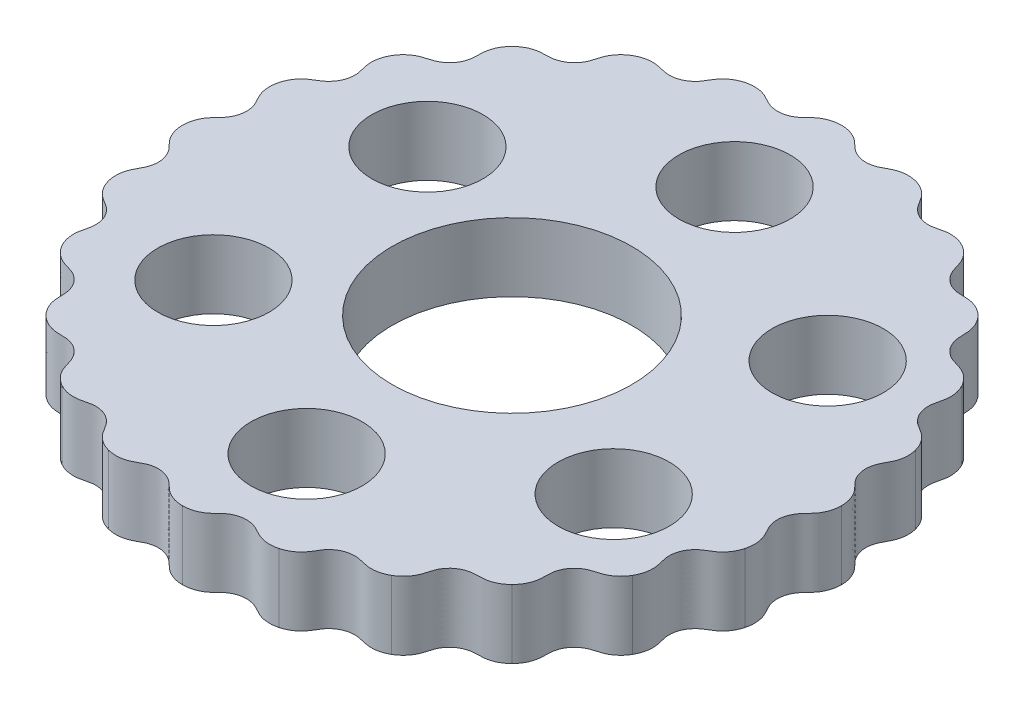
SolidWorks part; units mm, degrees
ref_plane "Front Plane" through (0, 0, 0) normal (0, 0, 1) x (1, 0, 0)
ref_plane "Top Plane" through (0, 0, 0) normal (0, 1, 0) x (1, 0, 0)
ref_plane "Right Plane" through (0, 0, 0) normal (1, 0, 0) x (0, 0, -1)
sketch "Sketch1" plane through (0, 0, 0) normal (0, 1, 0) x (1, 0, 0)
  line L0 (0, 0) -> (-1, 0) construction
  line L1 (40, 0) -> (41, 0) construction
  line L2 (-1, 0) -> (-1, 26) construction
  circle A0 centre (0, 0) radius 40 construction
  circle A1 centre (40, 0) radius 2.5 construction
  circle A2 centre (38.7433, -9.9476) radius 2.5 construction
  circle A3 centre (35.0523, -19.2701) radius 2.5 construction
  circle A4 centre (29.1587, -27.3819) radius 2.5 construction
  circle A5 centre (21.4331, -33.7731) radius 2.5 construction
  circle A6 centre (12.3607, -38.0423) radius 2.5 construction
  circle A7 centre (2.5116, -39.9211) radius 2.5 construction
  circle A8 centre (-7.4953, -39.2915) radius 2.5 construction
  circle A9 centre (-17.0312, -36.1931) radius 2.5 construction
  circle A10 centre (-25.497, -30.8205) radius 2.5 construction
  circle A11 centre (-32.3607, -23.5114) radius 2.5 construction
  circle A12 centre (-37.1911, -14.725) radius 2.5 construction
  circle A13 centre (-39.6846, -5.0133) radius 2.5 construction
  circle A14 centre (-39.6846, 5.0133) radius 2.5 construction
  circle A15 centre (-37.1911, 14.725) radius 2.5 construction
  circle A16 centre (-32.3607, 23.5114) radius 2.5 construction
  circle A17 centre (-25.497, 30.8205) radius 2.5 construction
  circle A18 centre (-17.0312, 36.1931) radius 2.5 construction
  circle A19 centre (-7.4953, 39.2915) radius 2.5 construction
  circle A20 centre (2.5116, 39.9211) radius 2.5 construction
  circle A21 centre (12.3607, 38.0423) radius 2.5 construction
  circle A22 centre (21.4331, 33.7731) radius 2.5 construction
  circle A23 centre (29.1587, 27.3819) radius 2.5 construction
  circle A24 centre (35.0523, 19.2701) radius 2.5 construction
  circle A25 centre (38.7433, 9.9476) radius 2.5 construction
  circle A26 centre (0, 0) radius 38.4 construction
  circle A27 centre (38.637, 10.3528) radius 1.6 construction
  circle A28 centre (39.603, 10.6116) radius 0.25 construction
  circle A29 centre (-1, 0) radius 14
  circle A30 centre (-1, 26) radius 6.5
  circle A31 centre (22.0167, 13.866) radius 6.5
  circle A32 centre (23.0167, -12.134) radius 6.5
  circle A33 centre (1, -26) radius 6.5
  circle A34 centre (-22.0167, -13.866) radius 6.5
  circle A35 centre (-23.0167, 12.134) radius 6.5
  spline S48 degree 3 poles (-38.1881, 9.9647) (-38.1134, 10.2441) (-37.9518, 10.654) (-37.653, 11.1446) (-37.3903, 11.4799) (-37.1455, 11.7256) (-36.9277, 11.9083) (-36.7529, 12.0385) (-36.5906, 12.1462) (-36.4589, 12.2267) (-36.305, 12.3174) (-36.1077, 12.438) (-35.8562, 12.5947) (-35.414, 12.9369) (-35.0082, 13.4243) (-34.7303, 13.9227) (-34.557, 14.4369) (-34.4576, 15.2234) (-34.5769, 15.8673) (-34.6328, 16.0713) (-34.6733, 16.2389) (-34.7113, 16.3925) (-34.7527, 16.5721) (-34.7948, 16.7807) (-34.8258, 16.9881) (-34.85, 17.2627) (-34.8492, 17.6154) (-34.7979, 18.0376) (-34.6627, 18.5948) (-34.4867, 18.9996) (-34.3419, 19.2502) knots -0.000084 -0.000084 -0.000084 -0.000084 0.124937 0.187447 0.249958 0.312468 0.343724 0.374979 0.406234 0.421862 0.437489 0.453117 0.468745 0.484372 0.492186 0.5 0.507814 0.515628 0.531255 0.546883 0.562511 0.578138 0.593766 0.625021 0.656276 0.687532 0.750042 0.812553 0.875063 1.000084 1.000084 1.000084 1.000084
  spline S49 degree 3 poles (-34.3419, 19.2502) (-34.1974, 19.5007) (-33.9353, 19.8548) (-33.5196, 20.2513) (-33.1791, 20.5073) (-32.879, 20.6812) (-32.6214, 20.8013) (-32.4189, 20.8818) (-32.2342, 20.9438) (-32.0861, 20.9876) (-31.914, 21.0353) (-31.6923, 21.1008) (-31.4088, 21.187) (-30.893, 21.4031) (-30.3749, 21.7688) (-29.9775, 22.1783) (-29.677, 22.6302) (-29.3775, 23.3642) (-29.326, 24.017) (-29.3272, 24.2285) (-29.323, 24.4009) (-29.3199, 24.559) (-29.3134, 24.7432) (-29.3001, 24.9557) (-29.2764, 25.164) (-29.2287, 25.4355) (-29.1366, 25.776) (-28.9778, 26.1705) (-28.703, 26.6737) (-28.4282, 27.0192) (-28.2235, 27.2237) knots -0.000084 -0.000084 -0.000084 -0.000084 0.124937 0.187447 0.249958 0.312468 0.343724 0.374979 0.406234 0.421862 0.437489 0.453117 0.468745 0.484372 0.492186 0.5 0.507814 0.515628 0.531255 0.546883 0.562511 0.578138 0.593766 0.625021 0.656276 0.687532 0.750042 0.812553 0.875063 1.000084 1.000084 1.000084 1.000084
  spline S50 degree 3 poles (-28.2235, 27.2237) (-28.0191, 27.4283) (-27.6742, 27.7026) (-27.1701, 27.978) (-26.7749, 28.1371) (-26.4401, 28.2274) (-26.1602, 28.2767) (-25.9437, 28.3021) (-25.7492, 28.3142) (-25.5949, 28.3181) (-25.4163, 28.3197) (-25.1852, 28.3255) (-24.889, 28.3354) (-24.3349, 28.4107) (-23.7398, 28.6298) (-23.25, 28.9226) (-22.8428, 29.2812) (-22.3634, 29.9127) (-22.1448, 30.5299) (-22.0912, 30.7346) (-22.0425, 30.9) (-21.9986, 31.0519) (-21.9447, 31.2282) (-21.8768, 31.43) (-21.8, 31.625) (-21.6836, 31.8749) (-21.5066, 32.18) (-21.251, 32.5199) (-20.8553, 32.9349) (-20.5005, 33.1974) (-20.2498, 33.3421) knots -0.000084 -0.000084 -0.000084 -0.000084 0.124937 0.187447 0.249958 0.312468 0.343724 0.374979 0.406234 0.421862 0.437489 0.453117 0.468745 0.484372 0.492186 0.5 0.507814 0.515628 0.531255 0.546883 0.562511 0.578138 0.593766 0.625021 0.656276 0.687532 0.750042 0.812553 0.875063 1.000084 1.000084 1.000084 1.000084
  spline S51 degree 3 poles (-20.2498, 33.3421) (-19.9994, 33.4868) (-19.5954, 33.6624) (-19.0372, 33.798) (-18.6143, 33.8494) (-18.2675, 33.85) (-17.9843, 33.8252) (-17.7687, 33.7936) (-17.5777, 33.755) (-17.4276, 33.7188) (-17.2547, 33.6741) (-17.0299, 33.6199) (-16.7413, 33.5529) (-16.1866, 33.4821) (-15.555, 33.5398) (-15.0061, 33.6958) (-14.52, 33.9368) (-13.8935, 34.4227) (-13.5226, 34.9623) (-13.4179, 35.1461) (-13.328, 35.2933) (-13.2462, 35.4287) (-13.1485, 35.585) (-13.0308, 35.7623) (-12.9061, 35.9308) (-12.729, 36.1421) (-12.479, 36.391) (-12.1442, 36.6532) (-11.6546, 36.9516) (-11.2439, 37.1134) (-10.9644, 37.1882) knots -0.000084 -0.000084 -0.000084 -0.000084 0.124937 0.187447 0.249958 0.312468 0.343724 0.374979 0.406234 0.421862 0.437489 0.453117 0.468745 0.484372 0.492186 0.5 0.507814 0.515628 0.531255 0.546883 0.562511 0.578138 0.593766 0.625021 0.656276 0.687532 0.750042 0.812553 0.875063 1.000084 1.000084 1.000084 1.000084
  spline S52 degree 3 poles (-10.9644, 37.1882) (-10.685, 37.2632) (-10.2493, 37.3283) (-9.675, 37.3147) (-9.2532, 37.2549) (-8.9181, 37.1657) (-8.651, 37.0685) (-8.4509, 36.9822) (-8.2764, 36.8954) (-8.1408, 36.8217) (-7.9853, 36.7337) (-7.7822, 36.6232) (-7.5208, 36.4837) (-7.0033, 36.2718) (-6.3783, 36.1641) (-5.8077, 36.1727) (-5.2758, 36.2797) (-4.5449, 36.5868) (-4.047, 37.0121) (-3.8982, 37.1625) (-3.7734, 37.2814) (-3.6593, 37.391) (-3.5245, 37.5167) (-3.3649, 37.6576) (-3.2008, 37.7881) (-2.9751, 37.9463) (-2.6692, 38.122) (-2.2779, 38.2886) (-1.7278, 38.4501) (-1.2892, 38.5001) (-0.9998, 38.5) knots -0.000084 -0.000084 -0.000084 -0.000084 0.124937 0.187447 0.249958 0.312468 0.343724 0.374979 0.406234 0.421862 0.437489 0.453117 0.468745 0.484372 0.492186 0.5 0.507814 0.515628 0.531255 0.546883 0.562511 0.578138 0.593766 0.625021 0.656276 0.687532 0.750042 0.812553 0.875063 1.000084 1.000084 1.000084 1.000084
  spline S53 degree 3 poles (-0.9998, 38.5) (-0.7106, 38.5001) (-0.2728, 38.4502) (0.2783, 38.2885) (0.6703, 38.1215) (0.9709, 37.9486) (1.2037, 37.7856) (1.3747, 37.6505) (1.5208, 37.5215) (1.6327, 37.4152) (1.7601, 37.29) (1.9277, 37.1307) (2.1441, 36.9283) (2.5891, 36.5896) (3.1649, 36.3238) (3.7182, 36.1844) (4.2598, 36.1501) (5.0452, 36.2577) (5.6363, 36.5395) (5.8189, 36.6464) (5.9703, 36.7289) (6.1088, 36.8053) (6.2716, 36.8918) (6.4622, 36.9865) (6.6544, 37.0701) (6.9134, 37.1645) (7.2543, 37.255) (7.6754, 37.3147) (8.2486, 37.3283) (8.6852, 37.2631) (8.9647, 37.1881) knots -0.000084 -0.000084 -0.000084 -0.000084 0.124937 0.187447 0.249958 0.312468 0.343724 0.374979 0.406234 0.421862 0.437489 0.453117 0.468745 0.484372 0.492186 0.5 0.507814 0.515628 0.531255 0.546883 0.562511 0.578138 0.593766 0.625021 0.656276 0.687532 0.750042 0.812553 0.875063 1.000084 1.000084 1.000084 1.000084
  spline S54 degree 3 poles (8.9647, 37.1881) (9.2441, 37.1134) (9.654, 36.9518) (10.1446, 36.653) (10.4799, 36.3903) (10.7256, 36.1455) (10.9083, 35.9277) (11.0385, 35.7529) (11.1462, 35.5906) (11.2267, 35.4589) (11.3174, 35.305) (11.438, 35.1077) (11.5947, 34.8562) (11.9369, 34.414) (12.4243, 34.0082) (12.9227, 33.7303) (13.4369, 33.557) (14.2234, 33.4576) (14.8673, 33.5769) (15.0713, 33.6328) (15.2389, 33.6733) (15.3925, 33.7113) (15.5721, 33.7527) (15.7807, 33.7948) (15.9881, 33.8258) (16.2627, 33.85) (16.6154, 33.8492) (17.0376, 33.7979) (17.5948, 33.6627) (17.9996, 33.4867) (18.2502, 33.3419) knots -0.000084 -0.000084 -0.000084 -0.000084 0.124937 0.187447 0.249958 0.312468 0.343724 0.374979 0.406234 0.421862 0.437489 0.453117 0.468745 0.484372 0.492186 0.5 0.507814 0.515628 0.531255 0.546883 0.562511 0.578138 0.593766 0.625021 0.656276 0.687532 0.750042 0.812553 0.875063 1.000084 1.000084 1.000084 1.000084
  spline S55 degree 3 poles (18.2502, 33.3419) (18.5007, 33.1974) (18.8548, 32.9353) (19.2513, 32.5196) (19.5073, 32.1791) (19.6812, 31.879) (19.8013, 31.6214) (19.8818, 31.4189) (19.9438, 31.2342) (19.9876, 31.0861) (20.0353, 30.914) (20.1008, 30.6923) (20.187, 30.4088) (20.4031, 29.893) (20.7688, 29.3749) (21.1783, 28.9775) (21.6302, 28.677) (22.3642, 28.3775) (23.017, 28.326) (23.2285, 28.3272) (23.4009, 28.323) (23.559, 28.3199) (23.7432, 28.3134) (23.9557, 28.3001) (24.164, 28.2764) (24.4355, 28.2287) (24.776, 28.1366) (25.1705, 27.9778) (25.6737, 27.703) (26.0192, 27.4282) (26.2237, 27.2235) knots -0.000084 -0.000084 -0.000084 -0.000084 0.124937 0.187447 0.249958 0.312468 0.343724 0.374979 0.406234 0.421862 0.437489 0.453117 0.468745 0.484372 0.492186 0.5 0.507814 0.515628 0.531255 0.546883 0.562511 0.578138 0.593766 0.625021 0.656276 0.687532 0.750042 0.812553 0.875063 1.000084 1.000084 1.000084 1.000084
  spline S56 degree 3 poles (26.2237, 27.2235) (26.4283, 27.0191) (26.7026, 26.6742) (26.978, 26.1701) (27.1371, 25.7749) (27.2274, 25.4401) (27.2767, 25.1602) (27.3021, 24.9437) (27.3142, 24.7492) (27.3181, 24.5949) (27.3197, 24.4163) (27.3255, 24.1852) (27.3354, 23.889) (27.4107, 23.3349) (27.6298, 22.7398) (27.9226, 22.25) (28.2812, 21.8428) (28.9127, 21.3634) (29.5299, 21.1448) (29.7346, 21.0912) (29.9, 21.0425) (30.0519, 20.9986) (30.2282, 20.9447) (30.43, 20.8768) (30.625, 20.8) (30.8749, 20.6836) (31.18, 20.5066) (31.5199, 20.251) (31.9349, 19.8553) (32.1974, 19.5005) (32.3421, 19.2498) knots -0.000084 -0.000084 -0.000084 -0.000084 0.124937 0.187447 0.249958 0.312468 0.343724 0.374979 0.406234 0.421862 0.437489 0.453117 0.468745 0.484372 0.492186 0.5 0.507814 0.515628 0.531255 0.546883 0.562511 0.578138 0.593766 0.625021 0.656276 0.687532 0.750042 0.812553 0.875063 1.000084 1.000084 1.000084 1.000084
  spline S57 degree 3 poles (32.3421, 19.2498) (32.4868, 18.9994) (32.6624, 18.5954) (32.798, 18.0372) (32.8494, 17.6143) (32.85, 17.2675) (32.8252, 16.9843) (32.7936, 16.7687) (32.755, 16.5777) (32.7188, 16.4276) (32.6741, 16.2547) (32.6199, 16.0299) (32.5529, 15.7413) (32.4821, 15.1866) (32.5398, 14.555) (32.6958, 14.0061) (32.9368, 13.52) (33.4227, 12.8935) (33.9623, 12.5226) (34.1461, 12.4179) (34.2933, 12.328) (34.4287, 12.2462) (34.585, 12.1485) (34.7623, 12.0308) (34.9308, 11.9061) (35.1421, 11.729) (35.391, 11.479) (35.6532, 11.1442) (35.9516, 10.6546) (36.1134, 10.2439) (36.1882, 9.9644) knots -0.000084 -0.000084 -0.000084 -0.000084 0.124937 0.187447 0.249958 0.312468 0.343724 0.374979 0.406234 0.421862 0.437489 0.453117 0.468745 0.484372 0.492186 0.5 0.507814 0.515628 0.531255 0.546883 0.562511 0.578138 0.593766 0.625021 0.656276 0.687532 0.750042 0.812553 0.875063 1.000084 1.000084 1.000084 1.000084
  spline S58 degree 3 poles (36.1882, 9.9644) (36.2632, 9.685) (36.3283, 9.2493) (36.3147, 8.675) (36.2549, 8.2532) (36.1657, 7.9181) (36.0685, 7.651) (35.9822, 7.4509) (35.8954, 7.2764) (35.8217, 7.1408) (35.7337, 6.9853) (35.6232, 6.7822) (35.4837, 6.5208) (35.2718, 6.0033) (35.1641, 5.3783) (35.1727, 4.8077) (35.2797, 4.2758) (35.5868, 3.5449) (36.0121, 3.047) (36.1625, 2.8982) (36.2814, 2.7734) (36.391, 2.6593) (36.5167, 2.5245) (36.6576, 2.3649) (36.7881, 2.2008) (36.9463, 1.9751) (37.122, 1.6692) (37.2886, 1.2779) (37.4501, 0.7278) (37.5001, 0.2892) (37.5, -0.0002) knots -0.000084 -0.000084 -0.000084 -0.000084 0.124937 0.187447 0.249958 0.312468 0.343724 0.374979 0.406234 0.421862 0.437489 0.453117 0.468745 0.484372 0.492186 0.5 0.507814 0.515628 0.531255 0.546883 0.562511 0.578138 0.593766 0.625021 0.656276 0.687532 0.750042 0.812553 0.875063 1.000084 1.000084 1.000084 1.000084
  spline S59 degree 3 poles (37.5, -0.0002) (37.5001, -0.2894) (37.4502, -0.7272) (37.2885, -1.2783) (37.1215, -1.6703) (36.9486, -1.9709) (36.7856, -2.2037) (36.6505, -2.3747) (36.5215, -2.5208) (36.4152, -2.6327) (36.29, -2.7601) (36.1307, -2.9277) (35.9283, -3.1441) (35.5896, -3.5891) (35.3238, -4.1649) (35.1844, -4.7182) (35.1501, -5.2598) (35.2577, -6.0452) (35.5395, -6.6363) (35.6464, -6.8189) (35.7289, -6.9703) (35.8053, -7.1088) (35.8918, -7.2716) (35.9865, -7.4622) (36.0701, -7.6544) (36.1645, -7.9134) (36.255, -8.2543) (36.3147, -8.6754) (36.3283, -9.2486) (36.2631, -9.6852) (36.1881, -9.9647) knots -0.000084 -0.000084 -0.000084 -0.000084 0.124937 0.187447 0.249958 0.312468 0.343724 0.374979 0.406234 0.421862 0.437489 0.453117 0.468745 0.484372 0.492186 0.5 0.507814 0.515628 0.531255 0.546883 0.562511 0.578138 0.593766 0.625021 0.656276 0.687532 0.750042 0.812553 0.875063 1.000084 1.000084 1.000084 1.000084
  spline S60 degree 3 poles (36.1881, -9.9647) (36.1134, -10.2441) (35.9518, -10.654) (35.653, -11.1446) (35.3903, -11.4799) (35.1455, -11.7256) (34.9277, -11.9083) (34.7529, -12.0385) (34.5906, -12.1462) (34.4589, -12.2267) (34.305, -12.3174) (34.1077, -12.438) (33.8562, -12.5947) (33.414, -12.9369) (33.0082, -13.4243) (32.7303, -13.9227) (32.557, -14.4369) (32.4576, -15.2234) (32.5769, -15.8673) (32.6328, -16.0713) (32.6733, -16.2389) (32.7113, -16.3925) (32.7527, -16.5721) (32.7948, -16.7807) (32.8258, -16.9881) (32.85, -17.2627) (32.8492, -17.6154) (32.7979, -18.0376) (32.6627, -18.5948) (32.4867, -18.9996) (32.3419, -19.2502) knots -0.000084 -0.000084 -0.000084 -0.000084 0.124937 0.187447 0.249958 0.312468 0.343724 0.374979 0.406234 0.421862 0.437489 0.453117 0.468745 0.484372 0.492186 0.5 0.507814 0.515628 0.531255 0.546883 0.562511 0.578138 0.593766 0.625021 0.656276 0.687532 0.750042 0.812553 0.875063 1.000084 1.000084 1.000084 1.000084
  spline S61 degree 3 poles (32.3419, -19.2502) (32.1974, -19.5007) (31.9353, -19.8548) (31.5196, -20.2513) (31.1791, -20.5073) (30.879, -20.6812) (30.6214, -20.8013) (30.4189, -20.8818) (30.2342, -20.9438) (30.0861, -20.9876) (29.914, -21.0353) (29.6923, -21.1008) (29.4088, -21.187) (28.893, -21.4031) (28.3749, -21.7688) (27.9775, -22.1783) (27.677, -22.6302) (27.3775, -23.3642) (27.326, -24.017) (27.3272, -24.2285) (27.323, -24.4009) (27.3199, -24.559) (27.3134, -24.7432) (27.3001, -24.9557) (27.2764, -25.164) (27.2287, -25.4355) (27.1366, -25.776) (26.9778, -26.1705) (26.703, -26.6737) (26.4282, -27.0192) (26.2235, -27.2237) knots -0.000084 -0.000084 -0.000084 -0.000084 0.124937 0.187447 0.249958 0.312468 0.343724 0.374979 0.406234 0.421862 0.437489 0.453117 0.468745 0.484372 0.492186 0.5 0.507814 0.515628 0.531255 0.546883 0.562511 0.578138 0.593766 0.625021 0.656276 0.687532 0.750042 0.812553 0.875063 1.000084 1.000084 1.000084 1.000084
  spline S62 degree 3 poles (26.2235, -27.2237) (26.0191, -27.4283) (25.6742, -27.7026) (25.1701, -27.978) (24.7749, -28.1371) (24.4401, -28.2274) (24.1602, -28.2767) (23.9437, -28.3021) (23.7492, -28.3142) (23.5949, -28.3181) (23.4163, -28.3197) (23.1852, -28.3255) (22.889, -28.3354) (22.3349, -28.4107) (21.7398, -28.6298) (21.25, -28.9226) (20.8428, -29.2812) (20.3634, -29.9127) (20.1448, -30.5299) (20.0912, -30.7346) (20.0425, -30.9) (19.9986, -31.0519) (19.9447, -31.2282) (19.8768, -31.43) (19.8, -31.625) (19.6836, -31.8749) (19.5066, -32.18) (19.251, -32.5199) (18.8553, -32.9349) (18.5005, -33.1974) (18.2498, -33.3421) knots -0.000084 -0.000084 -0.000084 -0.000084 0.124937 0.187447 0.249958 0.312468 0.343724 0.374979 0.406234 0.421862 0.437489 0.453117 0.468745 0.484372 0.492186 0.5 0.507814 0.515628 0.531255 0.546883 0.562511 0.578138 0.593766 0.625021 0.656276 0.687532 0.750042 0.812553 0.875063 1.000084 1.000084 1.000084 1.000084
  spline S63 degree 3 poles (18.2498, -33.3421) (17.9994, -33.4868) (17.5954, -33.6624) (17.0372, -33.798) (16.6143, -33.8494) (16.2675, -33.85) (15.9843, -33.8252) (15.7687, -33.7936) (15.5777, -33.755) (15.4276, -33.7188) (15.2547, -33.6741) (15.0299, -33.6199) (14.7413, -33.5529) (14.1866, -33.4821) (13.555, -33.5398) (13.0061, -33.6958) (12.52, -33.9368) (11.8935, -34.4227) (11.5226, -34.9623) (11.4179, -35.1461) (11.328, -35.2933) (11.2462, -35.4287) (11.1485, -35.585) (11.0308, -35.7623) (10.9061, -35.9308) (10.729, -36.1421) (10.479, -36.391) (10.1442, -36.6532) (9.6546, -36.9516) (9.2439, -37.1134) (8.9644, -37.1882) knots -0.000084 -0.000084 -0.000084 -0.000084 0.124937 0.187447 0.249958 0.312468 0.343724 0.374979 0.406234 0.421862 0.437489 0.453117 0.468745 0.484372 0.492186 0.5 0.507814 0.515628 0.531255 0.546883 0.562511 0.578138 0.593766 0.625021 0.656276 0.687532 0.750042 0.812553 0.875063 1.000084 1.000084 1.000084 1.000084
  spline S64 degree 3 poles (8.9644, -37.1882) (8.685, -37.2632) (8.2493, -37.3283) (7.675, -37.3147) (7.2532, -37.2549) (6.9181, -37.1657) (6.651, -37.0685) (6.4509, -36.9822) (6.2764, -36.8954) (6.1408, -36.8217) (5.9853, -36.7337) (5.7822, -36.6232) (5.5208, -36.4837) (5.0033, -36.2718) (4.3783, -36.1641) (3.8077, -36.1727) (3.2758, -36.2797) (2.5449, -36.5868) (2.047, -37.0121) (1.8982, -37.1625) (1.7734, -37.2814) (1.6593, -37.391) (1.5245, -37.5167) (1.3649, -37.6576) (1.2008, -37.7881) (0.9751, -37.9463) (0.6692, -38.122) (0.2779, -38.2886) (-0.2722, -38.4501) (-0.7108, -38.5001) (-1.0002, -38.5) knots -0.000084 -0.000084 -0.000084 -0.000084 0.124937 0.187447 0.249958 0.312468 0.343724 0.374979 0.406234 0.421862 0.437489 0.453117 0.468745 0.484372 0.492186 0.5 0.507814 0.515628 0.531255 0.546883 0.562511 0.578138 0.593766 0.625021 0.656276 0.687532 0.750042 0.812553 0.875063 1.000084 1.000084 1.000084 1.000084
  spline S65 degree 3 poles (-1.0002, -38.5) (-1.2894, -38.5001) (-1.7272, -38.4502) (-2.2783, -38.2885) (-2.6703, -38.1215) (-2.9709, -37.9486) (-3.2037, -37.7856) (-3.3747, -37.6505) (-3.5208, -37.5215) (-3.6327, -37.4152) (-3.7601, -37.29) (-3.9277, -37.1307) (-4.1441, -36.9283) (-4.5891, -36.5896) (-5.1649, -36.3238) (-5.7182, -36.1844) (-6.2598, -36.1501) (-7.0452, -36.2577) (-7.6363, -36.5395) (-7.8189, -36.6464) (-7.9703, -36.7289) (-8.1088, -36.8053) (-8.2716, -36.8918) (-8.4622, -36.9865) (-8.6544, -37.0701) (-8.9134, -37.1645) (-9.2543, -37.255) (-9.6754, -37.3147) (-10.2486, -37.3283) (-10.6852, -37.2631) (-10.9647, -37.1881) knots -0.000084 -0.000084 -0.000084 -0.000084 0.124937 0.187447 0.249958 0.312468 0.343724 0.374979 0.406234 0.421862 0.437489 0.453117 0.468745 0.484372 0.492186 0.5 0.507814 0.515628 0.531255 0.546883 0.562511 0.578138 0.593766 0.625021 0.656276 0.687532 0.750042 0.812553 0.875063 1.000084 1.000084 1.000084 1.000084
  spline S66 degree 3 poles (-10.9647, -37.1881) (-11.2441, -37.1134) (-11.654, -36.9518) (-12.1446, -36.653) (-12.4799, -36.3903) (-12.7256, -36.1455) (-12.9083, -35.9277) (-13.0385, -35.7529) (-13.1462, -35.5906) (-13.2267, -35.4589) (-13.3174, -35.305) (-13.438, -35.1077) (-13.5947, -34.8562) (-13.9369, -34.414) (-14.4243, -34.0082) (-14.9227, -33.7303) (-15.4369, -33.557) (-16.2234, -33.4576) (-16.8673, -33.5769) (-17.0713, -33.6328) (-17.2389, -33.6733) (-17.3925, -33.7113) (-17.5721, -33.7527) (-17.7807, -33.7948) (-17.9881, -33.8258) (-18.2627, -33.85) (-18.6154, -33.8492) (-19.0376, -33.7979) (-19.5948, -33.6627) (-19.9996, -33.4867) (-20.2502, -33.3419) knots -0.000084 -0.000084 -0.000084 -0.000084 0.124937 0.187447 0.249958 0.312468 0.343724 0.374979 0.406234 0.421862 0.437489 0.453117 0.468745 0.484372 0.492186 0.5 0.507814 0.515628 0.531255 0.546883 0.562511 0.578138 0.593766 0.625021 0.656276 0.687532 0.750042 0.812553 0.875063 1.000084 1.000084 1.000084 1.000084
  spline S67 degree 3 poles (-20.2502, -33.3419) (-20.5007, -33.1974) (-20.8548, -32.9353) (-21.2513, -32.5196) (-21.5073, -32.1791) (-21.6812, -31.879) (-21.8013, -31.6214) (-21.8818, -31.4189) (-21.9438, -31.2342) (-21.9876, -31.0861) (-22.0353, -30.914) (-22.1008, -30.6923) (-22.187, -30.4088) (-22.4031, -29.893) (-22.7688, -29.3749) (-23.1783, -28.9775) (-23.6302, -28.677) (-24.3642, -28.3775) (-25.017, -28.326) (-25.2285, -28.3272) (-25.4009, -28.323) (-25.559, -28.3199) (-25.7432, -28.3134) (-25.9557, -28.3001) (-26.164, -28.2764) (-26.4355, -28.2287) (-26.776, -28.1366) (-27.1705, -27.9778) (-27.6737, -27.703) (-28.0192, -27.4282) (-28.2237, -27.2235) knots -0.000084 -0.000084 -0.000084 -0.000084 0.124937 0.187447 0.249958 0.312468 0.343724 0.374979 0.406234 0.421862 0.437489 0.453117 0.468745 0.484372 0.492186 0.5 0.507814 0.515628 0.531255 0.546883 0.562511 0.578138 0.593766 0.625021 0.656276 0.687532 0.750042 0.812553 0.875063 1.000084 1.000084 1.000084 1.000084
  spline S68 degree 3 poles (-28.2237, -27.2235) (-28.4283, -27.0191) (-28.7026, -26.6742) (-28.978, -26.1701) (-29.1371, -25.7749) (-29.2274, -25.4401) (-29.2767, -25.1602) (-29.3021, -24.9437) (-29.3142, -24.7492) (-29.3181, -24.5949) (-29.3197, -24.4163) (-29.3255, -24.1852) (-29.3354, -23.889) (-29.4107, -23.3349) (-29.6298, -22.7398) (-29.9226, -22.25) (-30.2812, -21.8428) (-30.9127, -21.3634) (-31.5299, -21.1448) (-31.7346, -21.0912) (-31.9, -21.0425) (-32.0519, -20.9986) (-32.2282, -20.9447) (-32.43, -20.8768) (-32.625, -20.8) (-32.8749, -20.6836) (-33.18, -20.5066) (-33.5199, -20.251) (-33.9349, -19.8553) (-34.1974, -19.5005) (-34.3421, -19.2498) knots -0.000084 -0.000084 -0.000084 -0.000084 0.124937 0.187447 0.249958 0.312468 0.343724 0.374979 0.406234 0.421862 0.437489 0.453117 0.468745 0.484372 0.492186 0.5 0.507814 0.515628 0.531255 0.546883 0.562511 0.578138 0.593766 0.625021 0.656276 0.687532 0.750042 0.812553 0.875063 1.000084 1.000084 1.000084 1.000084
  spline S69 degree 3 poles (-34.3421, -19.2498) (-34.4868, -18.9994) (-34.6624, -18.5954) (-34.798, -18.0372) (-34.8494, -17.6143) (-34.85, -17.2675) (-34.8252, -16.9843) (-34.7936, -16.7687) (-34.755, -16.5777) (-34.7188, -16.4276) (-34.6741, -16.2547) (-34.6199, -16.0299) (-34.5529, -15.7413) (-34.4821, -15.1866) (-34.5398, -14.555) (-34.6958, -14.0061) (-34.9368, -13.52) (-35.4227, -12.8935) (-35.9623, -12.5226) (-36.1461, -12.4179) (-36.2933, -12.328) (-36.4287, -12.2462) (-36.585, -12.1485) (-36.7623, -12.0308) (-36.9308, -11.9061) (-37.1421, -11.729) (-37.391, -11.479) (-37.6532, -11.1442) (-37.9516, -10.6546) (-38.1134, -10.2439) (-38.1882, -9.9644) knots -0.000084 -0.000084 -0.000084 -0.000084 0.124937 0.187447 0.249958 0.312468 0.343724 0.374979 0.406234 0.421862 0.437489 0.453117 0.468745 0.484372 0.492186 0.5 0.507814 0.515628 0.531255 0.546883 0.562511 0.578138 0.593766 0.625021 0.656276 0.687532 0.750042 0.812553 0.875063 1.000084 1.000084 1.000084 1.000084
  spline S70 degree 3 poles (-38.1882, -9.9644) (-38.2632, -9.685) (-38.3283, -9.2493) (-38.3147, -8.675) (-38.2549, -8.2532) (-38.1657, -7.9181) (-38.0685, -7.651) (-37.9822, -7.4509) (-37.8954, -7.2764) (-37.8217, -7.1408) (-37.7337, -6.9853) (-37.6232, -6.7822) (-37.4837, -6.5208) (-37.2718, -6.0033) (-37.1641, -5.3783) (-37.1727, -4.8077) (-37.2797, -4.2758) (-37.5868, -3.5449) (-38.0121, -3.047) (-38.1625, -2.8982) (-38.2814, -2.7734) (-38.391, -2.6593) (-38.5167, -2.5245) (-38.6576, -2.3649) (-38.7881, -2.2008) (-38.9463, -1.9751) (-39.122, -1.6692) (-39.2886, -1.2779) (-39.4501, -0.7278) (-39.5001, -0.2892) (-39.5, 0.0002) knots -0.000084 -0.000084 -0.000084 -0.000084 0.124937 0.187447 0.249958 0.312468 0.343724 0.374979 0.406234 0.421862 0.437489 0.453117 0.468745 0.484372 0.492186 0.5 0.507814 0.515628 0.531255 0.546883 0.562511 0.578138 0.593766 0.625021 0.656276 0.687532 0.750042 0.812553 0.875063 1.000084 1.000084 1.000084 1.000084
  spline S71 degree 3 poles (-39.5, 0.0002) (-39.5001, 0.2894) (-39.4502, 0.7272) (-39.2885, 1.2783) (-39.1215, 1.6703) (-38.9486, 1.9709) (-38.7856, 2.2037) (-38.6505, 2.3747) (-38.5215, 2.5208) (-38.4152, 2.6327) (-38.29, 2.7601) (-38.1307, 2.9277) (-37.9283, 3.1441) (-37.5896, 3.5891) (-37.3238, 4.1649) (-37.1844, 4.7182) (-37.1501, 5.2598) (-37.2577, 6.0452) (-37.5395, 6.6363) (-37.6464, 6.8189) (-37.7289, 6.9703) (-37.8053, 7.1088) (-37.8918, 7.2716) (-37.9865, 7.4622) (-38.0701, 7.6544) (-38.1645, 7.9134) (-38.255, 8.2543) (-38.3147, 8.6754) (-38.3283, 9.2486) (-38.2631, 9.6852) (-38.1881, 9.9647) knots -0.000084 -0.000084 -0.000084 -0.000084 0.124937 0.187447 0.249958 0.312468 0.343724 0.374979 0.406234 0.421862 0.437489 0.453117 0.468745 0.484372 0.492186 0.5 0.507814 0.515628 0.531255 0.546883 0.562511 0.578138 0.593766 0.625021 0.656276 0.687532 0.750042 0.812553 0.875063 1.000084 1.000084 1.000084 1.000084
  point P55 (0, 0)
  point P60 (41, 0)
  point P63 (40.9002, 1.1207)
  point P64 (40.6184, 2.162)
  point P65 (40.204, 3.0594)
  point P66 (39.7289, 3.7751)
  point P67 (39.2742, 4.3054)
  point P68 (38.9149, 4.6811)
  point P69 (38.7057, 4.9619)
  point P70 (38.671, 5.2249)
  point P71 (38.8004, 5.5503)
  point P72 (39.0503, 6.0062)
  point P73 (39.3522, 6.6362)
  point P74 (39.6259, 7.4504)
  point P75 (39.794, 8.4245)
  point P76 (39.7966, 9.5032)
  point P77 (39.603, 10.6116)
  point P93 (0, 0)
  point P462 (0, 0)
  dimension "D1" = 80
  dimension "D2" = 5
  dimension "D4" = 76.8
  dimension "D6" = 0.5
  dimension "D8" = 28
  dimension "D10" = 13
  dimension "D3" = 1
  dimension "D5" = 1
  dimension "D9" = 26
  dimension "D7" = 25
  dimension "D11" = 6
extrude "Boss-Extrude1" add sketch "Sketch1" along normal blind 8
